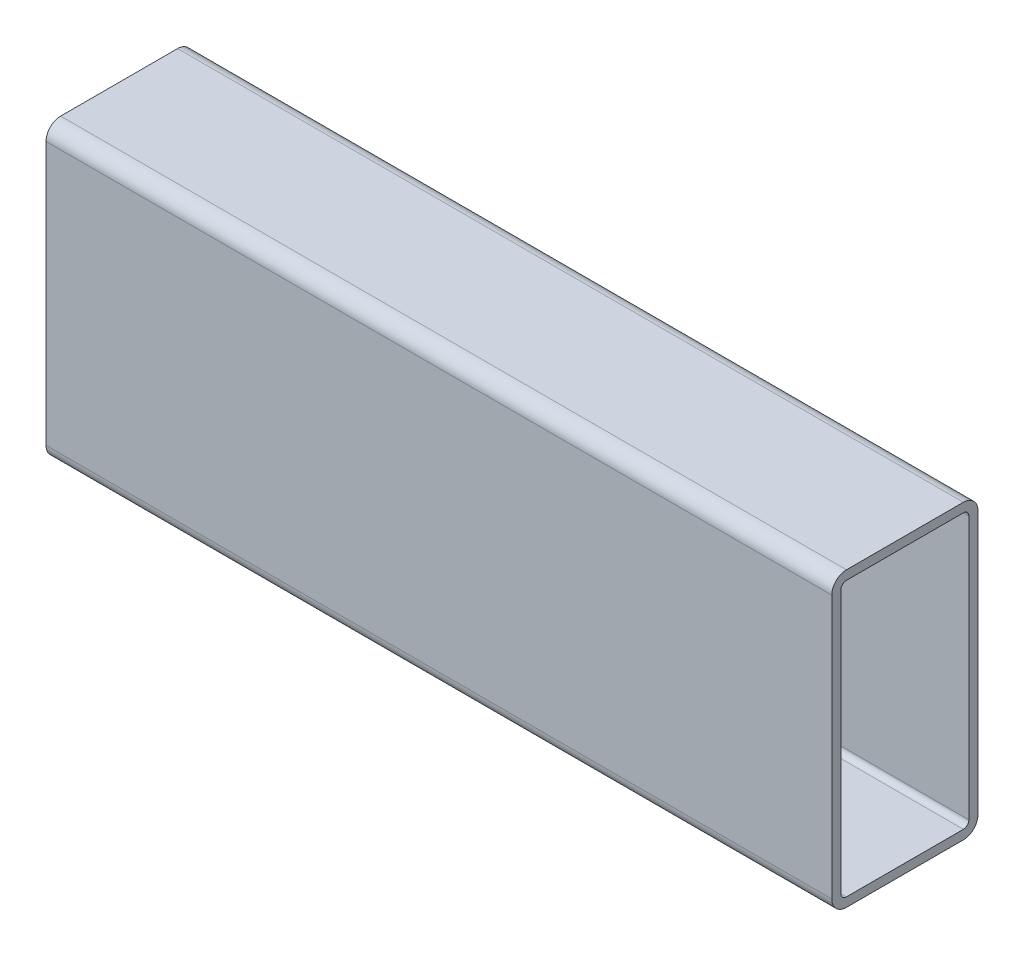
SolidWorks part; units mm, degrees
material "6061-T6 (SS)"
ref_plane "Front" through (0, 0, 0) normal (0, 0, 1) x (1, 0, 0)
ref_plane "Top" through (0, 0, 0) normal (0, 1, 0) x (1, 0, 0)
ref_plane "Right" through (0, 0, 0) normal (1, 0, 0) x (0, 0, -1)
sketch "Sketch1" plane through (0, 0, 0) normal (1, 0, 0) x (0, 0, -1)
  line L1 (-10.16, -25.4) -> (10.16, -25.4)
  line L2 (-12.7, -22.86) -> (-12.7, 22.86)
  line L3 (-10.16, 25.4) -> (10.16, 25.4)
  line L4 (12.7, -22.86) -> (12.7, 22.86)
  line L5 (-12.7, -25.4) -> (12.7, 25.4) construction
  line L6 (-12.7, 25.4) -> (12.7, -25.4) construction
  arc A0 (-10.16, -25.4) -> (-12.7, -22.86) centre (-10.16, -22.86) cw
  arc A1 (10.16, -25.4) -> (12.7, -22.86) centre (10.16, -22.86) ccw
  arc A2 (10.16, 25.4) -> (12.7, 22.86) centre (10.16, 22.86) cw
  arc A3 (-12.7, 22.86) -> (-10.16, 25.4) centre (-10.16, 22.86) cw
  point P0 (0, 0)
  dimension "D1" = 2.54
  dimension "D2" = 25.4
  dimension "D3" = 50.8
extrude "Extrude-Thin1" add sketch "Sketch1" along normal mid plane 136.525 thin thin type one direction reverse wall 1.5875
